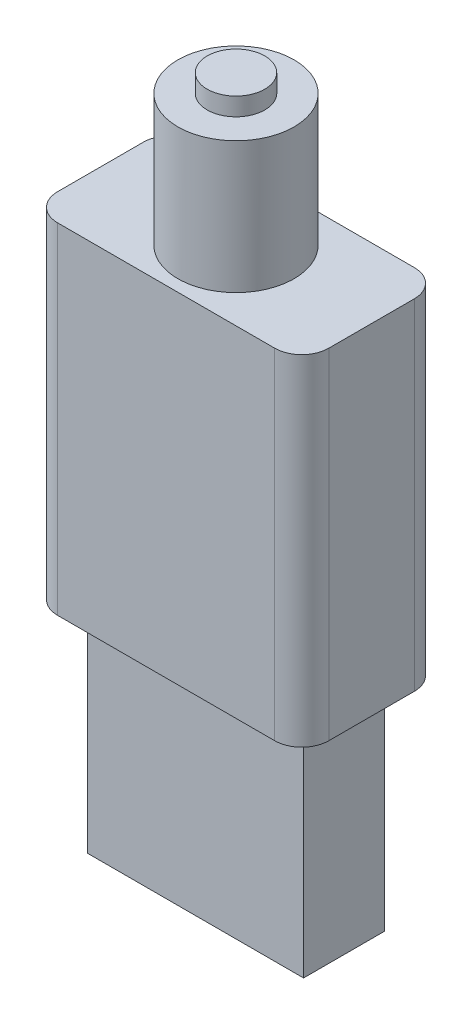
SolidWorks part; units mm, degrees
ref_plane "Front Plane" through (0, 0, 0) normal (0, 0, 1) x (1, 0, 0)
ref_plane "Top Plane" through (0, 0, 0) normal (0, 1, 0) x (1, 0, 0)
ref_plane "Right Plane" through (0, 0, 0) normal (1, 0, 0) x (0, 0, -1)
sketch "Sketch1" plane through (0, 0, 0) normal (0, 1, 0) x (1, 0, 0)
  line L1 (-6, -2.25) -> (6, -2.25)
  line L2 (-6, -2.25) -> (-6, 2.25)
  line L3 (-6, 2.25) -> (6, 2.25)
  line L4 (6, -2.25) -> (6, 2.25)
  line L5 (-6, -2.25) -> (6, 2.25) construction
  line L6 (-6, 2.25) -> (6, -2.25) construction
  point P0 (0, 0)
  dimension "D1" = 12
  dimension "D2" = 4.5
extrude "Boss-Extrude1" add sketch "Sketch1" along normal blind 12.23
sketch "Sketch2" plane through (0, 12.23, 0) normal (0, 1, 0) x (1, 0, 0)
  line L1 (-6.025, -3.875) -> (6.025, -3.875)
  line L2 (-7.525, -2.375) -> (-7.525, 2.375)
  line L3 (-6.025, 3.875) -> (6.025, 3.875)
  line L4 (7.525, -2.375) -> (7.525, 2.375)
  line L5 (-7.525, -3.875) -> (7.525, 3.875) construction
  line L6 (-7.525, 3.875) -> (7.525, -3.875) construction
  arc A0 (-6.025, -3.875) -> (-7.525, -2.375) centre (-6.025, -2.375) cw
  arc A1 (6.025, -3.875) -> (7.525, -2.375) centre (6.025, -2.375) ccw
  arc A2 (6.025, 3.875) -> (7.525, 2.375) centre (6.025, 2.375) cw
  arc A3 (-7.525, 2.375) -> (-6.025, 3.875) centre (-6.025, 2.375) cw
  point P0 (0, 0)
  dimension "D3" = 1.5
  dimension "D1" = 7.75
  dimension "D2" = 15.05
extrude "Boss-Extrude2" add sketch "Sketch2" along normal blind 18.87
sketch "Sketch3" plane through (0, 31.1, 0) normal (0, 1, 0) x (1, 0, 0)
  circle A0 centre (0, 0) radius 3.225
  dimension "D1" = 6.45
extrude "Boss-Extrude3" add sketch "Sketch3" along normal blind 7.3
sketch "Sketch4" plane through (0, 38.4, 0) normal (0, 1, 0) x (1, 0, 0)
  circle A0 centre (0, 0) radius 1.6
  dimension "D1" = 3.2
extrude "Boss-Extrude4" add sketch "Sketch4" along normal blind 1
